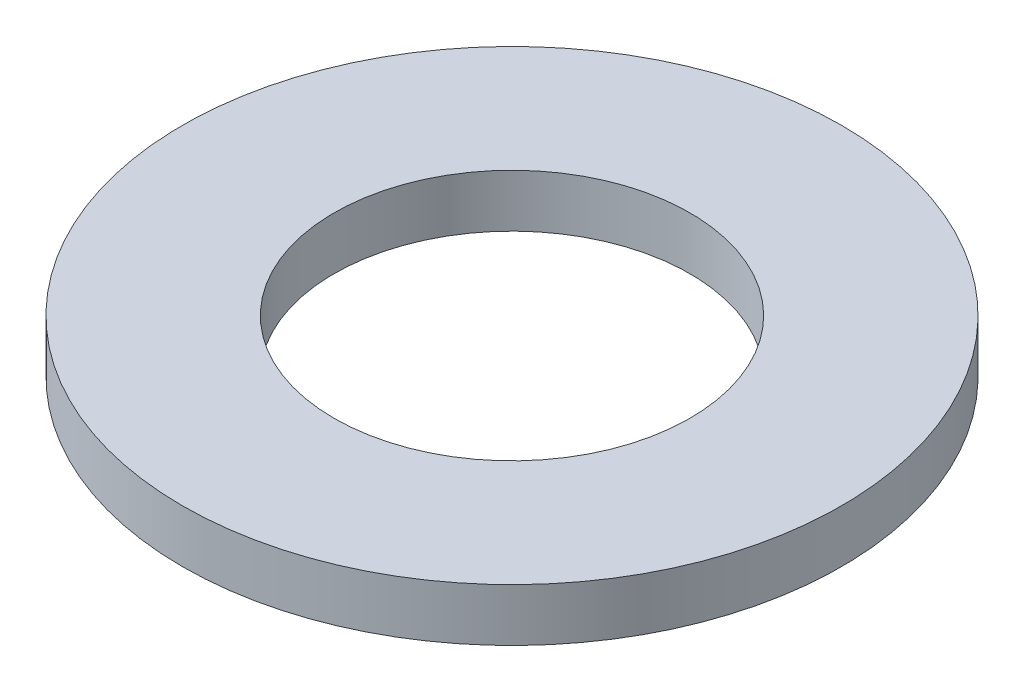
SolidWorks part; units mm, degrees
ref_plane "Front Plane" through (0, 0, 0) normal (0, 0, 1) x (1, 0, 0)
ref_plane "Top Plane" through (0, 0, 0) normal (0, 1, 0) x (1, 0, 0)
ref_plane "Right Plane" through (0, 0, 0) normal (1, 0, 0) x (0, 0, -1)
sketch "Sketch1" plane through (0, 0, 0) normal (0, 1, 0) x (1, 0, 0)
  circle A0 centre (0, 0) radius 6.75
  circle A1 centre (0, 0) radius 12.5
  dimension "D1" = 13.5
  dimension "D2" = 25
extrude "Boss-Extrude1" add sketch "Sketch1" along normal blind 2
